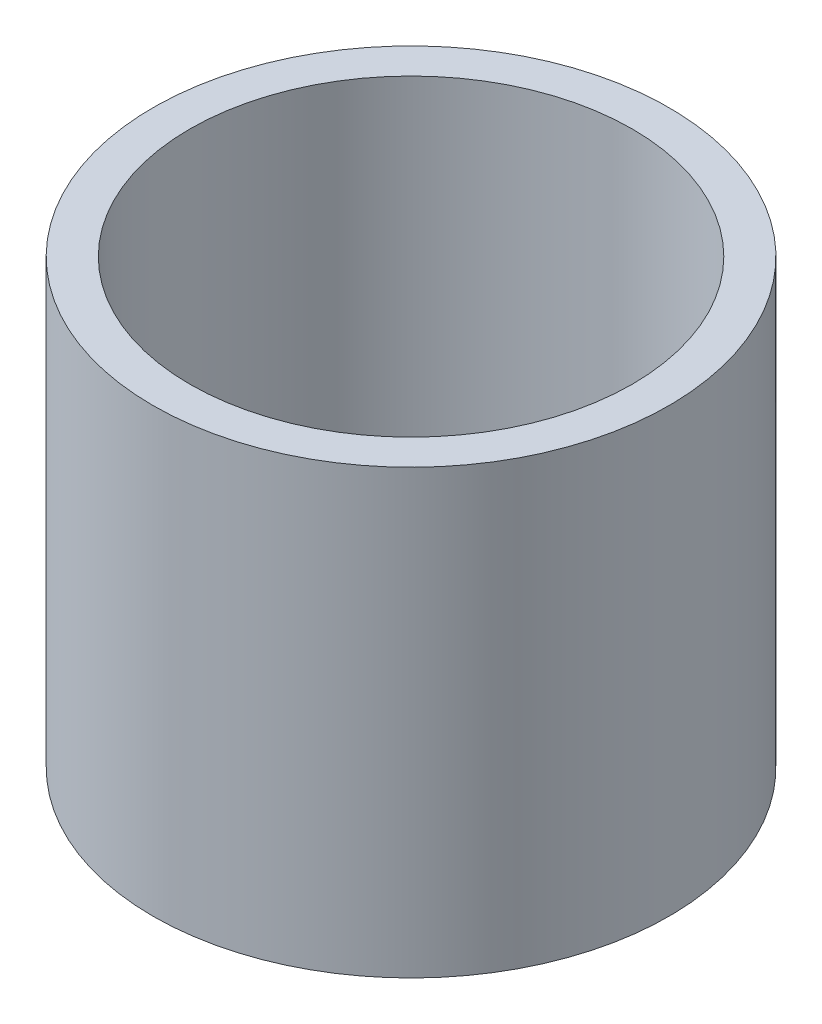
SolidWorks part; units mm, degrees
ref_plane "Front Plane" through (0, 0, 0) normal (0, 0, 1) x (1, 0, 0)
ref_plane "Top Plane" through (0, 0, 0) normal (0, 1, 0) x (1, 0, 0)
ref_plane "Right Plane" through (0, 0, 0) normal (1, 0, 0) x (0, 0, -1)
sketch "Sketch1" plane through (0, 0, 0) normal (0, 1, 0) x (1, 0, 0)
  circle A0 centre (0, 0) radius 30
  circle A1 centre (0, 0) radius 35
  dimension "D1" = 60
  dimension "D2" = 5
extrude "Boss-Extrude1" add sketch "Sketch1" along normal blind 60
